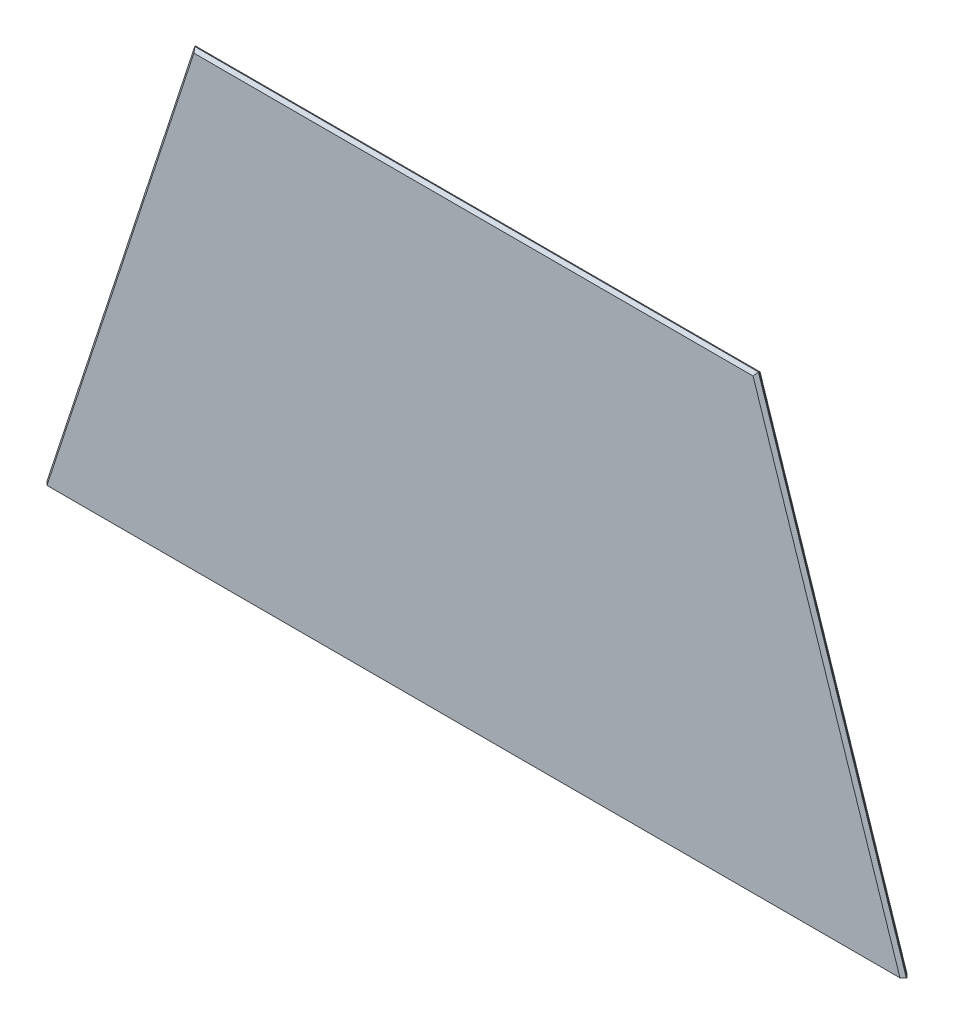
SolidWorks part; units mm, degrees
material "Printed Circuit Board"
ref_plane "Front Plane" through (0, 0, 0) normal (0, 0, 1) x (1, 0, 0)
ref_plane "Top Plane" through (0, 0, 0) normal (0, 1, 0) x (1, 0, 0)
ref_plane "Right Plane" through (0, 0, 0) normal (1, 0, 0) x (0, 0, -1)
sketch "Sketch1" plane through (0, 0, 0) normal (0, 0, 1) x (1, 0, 0)
  line L0 (0, 0) -> (193.675, 0)
  line L1 (193.675, 0) -> (127, 203.2)
  line L2 (127, 203.2) -> (0, 203.2)
  line L3 (0, 203.2) -> (-127, 203.2)
  line L4 (-127, 203.2) -> (-193.675, 0)
  line L5 (-193.675, 0) -> (0, 0)
  line L6 (0, 0) -> (0, 203.2) construction
  dimension "D1" = 203.2
  dimension "D2" = 387.35
  dimension "D3" = 254
extrude "Extrude1" add sketch "Sketch1" along normal mid plane 3.175
ref_plane "Plane1" through (0, 0, 0) normal (-1, 0, 0) x (0, 0, 1)
chamfer "Chamfer1" distance 1.397 angle 45 6 edges at (160.3375, 101.6, -1.5875) (0, 203.2, -1.5875) (-160.3375, 101.6, -1.5875) (160.3375, 101.6, 1.5875) (0, 203.2, 1.5875) (-160.3375, 101.6, 1.5875)
